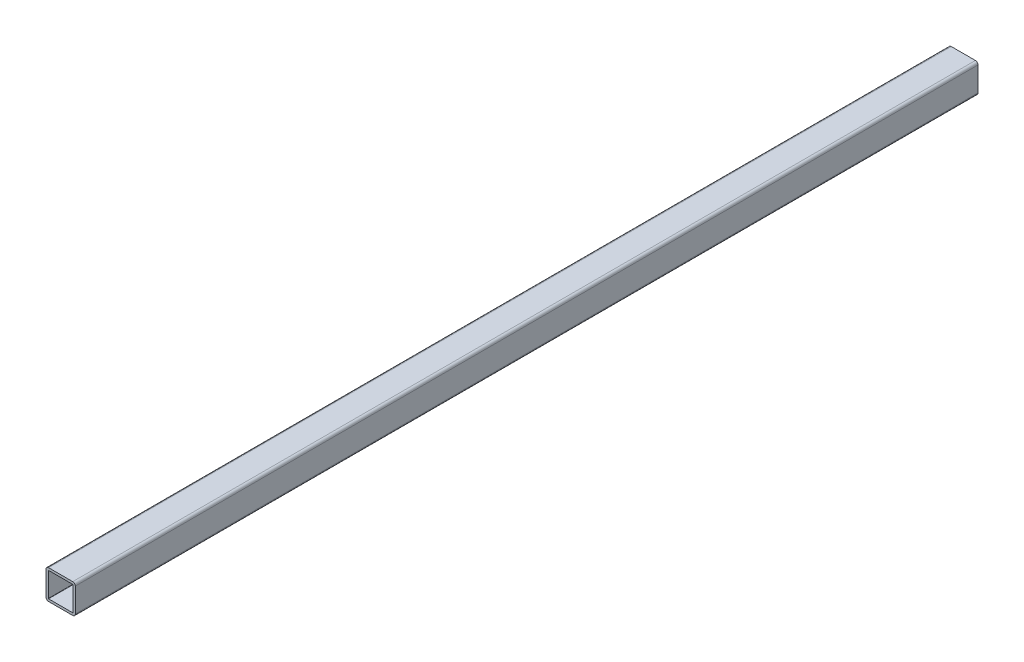
SolidWorks part; units mm, degrees
material "AISI 1020 Steel, Cold Rolled"
ref_plane "Front Plane" through (0, 0, 0) normal (0, 0, 1) x (1, 0, 0)
ref_plane "Top Plane" through (0, 0, 0) normal (0, 1, 0) x (1, 0, 0)
ref_plane "Right Plane" through (0, 0, 0) normal (1, 0, 0) x (0, 0, -1)
sketch "Sketch1" plane through (0, 0, 0) normal (0, 1, 0) x (1, 0, 0)
  line L0 (0, 0) -> (0, 770)
  dimension "D1" = 770
other "Structural Member1"
ref_plane "Plane1" through (0, 0, 0) normal (0, 0, -1) x (-1, 0, 0)
sketch "Sketch11" plane through (0, 0, 0) normal (0, 0, -1) x (-1, 0, 0)
  line L0 (-10.3, -10.5) -> (10.3, -10.5)
  line L1 (-10.5, -10.3) -> (-10.5, 10.3)
  line L2 (10.3, 10.5) -> (-10.3, 10.5)
  line L3 (10.5, 10.3) -> (10.5, -10.3)
  line L4 (-10.3, -12.5) -> (10.3, -12.5)
  line L5 (-12.5, -10.3) -> (-12.5, 10.3)
  line L6 (10.3, 12.5) -> (-10.3, 12.5)
  line L7 (12.5, 10.3) -> (12.5, -10.3)
  arc A0 (12.5, 10.3) -> (10.3, 12.5) centre (10.3, 10.3) ccw
  arc A1 (10.3, -12.5) -> (12.5, -10.3) centre (10.3, -10.3) ccw
  arc A2 (-12.5, -10.3) -> (-10.3, -12.5) centre (-10.3, -10.3) ccw
  arc A3 (-10.3, 12.5) -> (-12.5, 10.3) centre (-10.3, 10.3) ccw
  arc A4 (-10.3, 10.5) -> (-10.5, 10.3) centre (-10.3, 10.3) ccw
  arc A5 (10.5, 10.3) -> (10.3, 10.5) centre (10.3, 10.3) ccw
  arc A6 (10.3, -10.5) -> (10.5, -10.3) centre (10.3, -10.3) ccw
  arc A7 (-10.5, -10.3) -> (-10.3, -10.5) centre (-10.3, -10.3) ccw
  point P0 (-12.5, 0)
  point P1 (12.5, 0)
  point P2 (0, 12.5)
  point P3 (0, -12.5)
  point P4 (0, 0)
  point P5 (-12.5, -12.5)
  point P6 (12.5, -12.5)
  point P7 (12.5, 12.5)
  point P8 (-12.5, 12.5)
  point P33 (0, 0)
  dimension "D1" = 2.2
  dimension "Thickness" = 2
  dimension "V_leg" = 25
